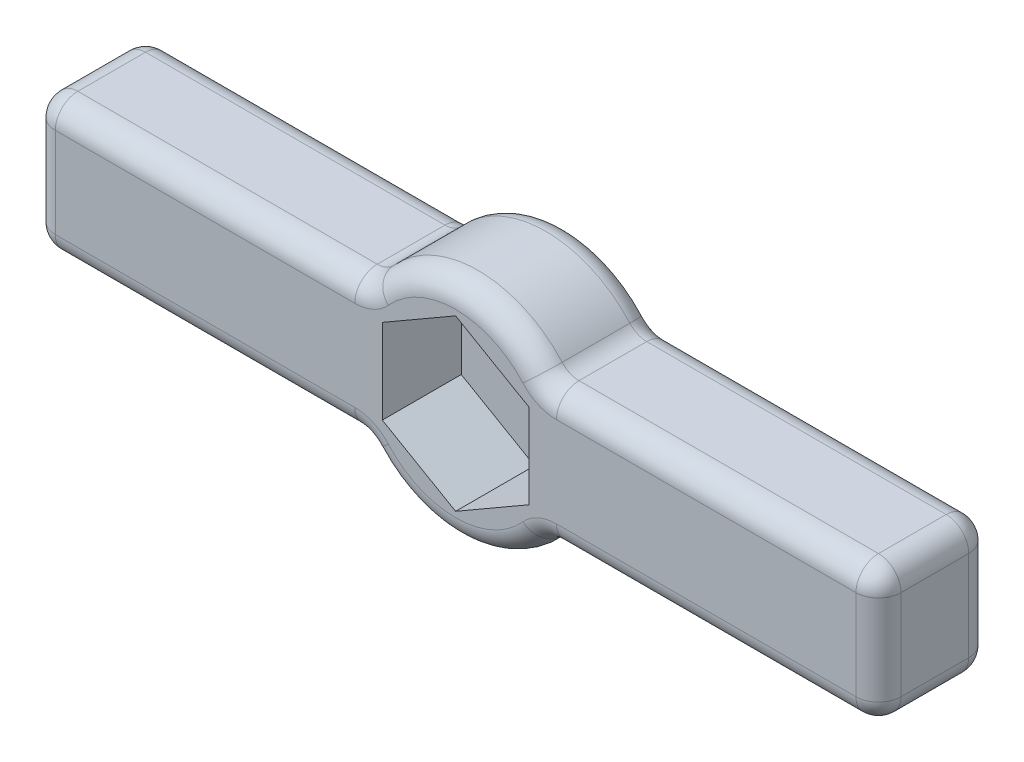
SolidWorks part; units mm, degrees
ref_plane "Front Plane" through (0, 0, 0) normal (0, 0, 1) x (1, 0, 0)
ref_plane "Top Plane" through (0, 0, 0) normal (0, 1, 0) x (1, 0, 0)
ref_plane "Right Plane" through (0, 0, 0) normal (1, 0, 0) x (0, 0, -1)
sketch "Sketch1" plane through (0, 0, 0) normal (0, 0, 1) x (1, 0, 0)
  line L1 (-37.5, -6) -> (37.5, -6)
  line L2 (-37.5, -6) -> (-37.5, 6)
  line L3 (-37.5, 6) -> (37.5, 6)
  line L4 (37.5, -6) -> (37.5, 6)
  line L5 (-37.5, -6) -> (37.5, 6) construction
  line L6 (-37.5, 6) -> (37.5, -6) construction
  point P0 (0, 0)
  dimension "D1" = 12
  dimension "D2" = 75
extrude "Boss-Extrude1" add sketch "Sketch1" along normal blind 10
sketch "Sketch2" plane through (0, 0, 10) normal (0, 0, 1) x (1, 0, 0)
  line L1 (0, -7.5056) -> (6.5, -3.7528)
  line L2 (6.5, -3.7528) -> (6.5, 3.7528)
  line L3 (6.5, 3.7528) -> (0, 7.5056)
  line L4 (0, 7.5056) -> (-6.5, 3.7528)
  line L5 (-6.5, 3.7528) -> (-6.5, -3.7528)
  line L6 (-6.5, -3.7528) -> (0, -7.5056)
  circle A0 centre (0, 0) radius 6.5 construction
  circle A1 centre (0, 0) radius 10.2013 construction
  dimension "D1" = 13
extrude "Cut-Extrude1" cut sketch "Sketch2" against normal blind 7
sketch "Sketch3" plane through (0, 0, 0) normal (0, 0, -1) x (-1, 0, 0)
  line L1 (0, -7.5056) -> (6.5, -3.7528)
  line L2 (6.5, -3.7528) -> (6.5, 3.7528)
  line L3 (6.5, 3.7528) -> (0, 7.5056)
  line L4 (0, 7.5056) -> (-6.5, 3.7528)
  line L5 (-6.5, 3.7528) -> (-6.5, -3.7528)
  line L6 (-6.5, -3.7528) -> (0, -7.5056)
  circle A0 centre (0, 0) radius 10
  circle A1 centre (0, 0) radius 6.5 construction
  dimension "D1" = 13
  dimension "D2" = 20
extrude "Boss-Extrude2" add sketch "Sketch3" against normal blind 10
sketch "Sketch4" plane through (0, 0, 0) normal (0, 0, -1) x (-1, 0, 0)
  line L0 (2.6077, 6) -> (0, 7.5056) construction
  line L1 (2.6077, 6) -> (0, 7.5056)
  line L2 (-2.6077, 6) -> (2.6077, 6) construction
  line L3 (-2.6077, 6) -> (2.6077, 6)
  line L4 (0, 7.5056) -> (-2.6077, 6) construction
  line L5 (0, 7.5056) -> (-2.6077, 6)
  line L6 (0, -7.5056) -> (2.6077, -6) construction
  line L7 (-2.6077, -6) -> (0, -7.5056) construction
  line L8 (2.6077, -6) -> (-2.6077, -6) construction
  line L9 (0, -7.5056) -> (2.6077, -6)
  line L10 (-2.6077, -6) -> (0, -7.5056)
  line L11 (2.6077, -6) -> (-2.6077, -6)
extrude "Boss-Extrude3" add sketch "Sketch4" against normal up to surface (3 mm away) up to face at (0, 0, 3)
fillet "Fillet1" radius 2 24 edges at (22.75, 6, 10) (37.5, 0, 10) (22.75, -6, 10) (0, -10, 10) (0, -10, 0) (-22.75, -6, 10) (-37.5, 0, 10) (-22.75, 6, 10) (0, 10, 10) (0, 10, 0) (-8, 6, 5) (8, 6, 5) (8, -6, 5) (-8, -6, 5) (-37.5, -6, 5) (-37.5, 6, 5) (-37.5, 0, 0) (-22.75, -6, 0) (-22.75, 6, 0) (22.75, 6, 0) (22.75, -6, 0) (37.5, 0, 0) (37.5, 6, 5) (37.5, -6, 5)
